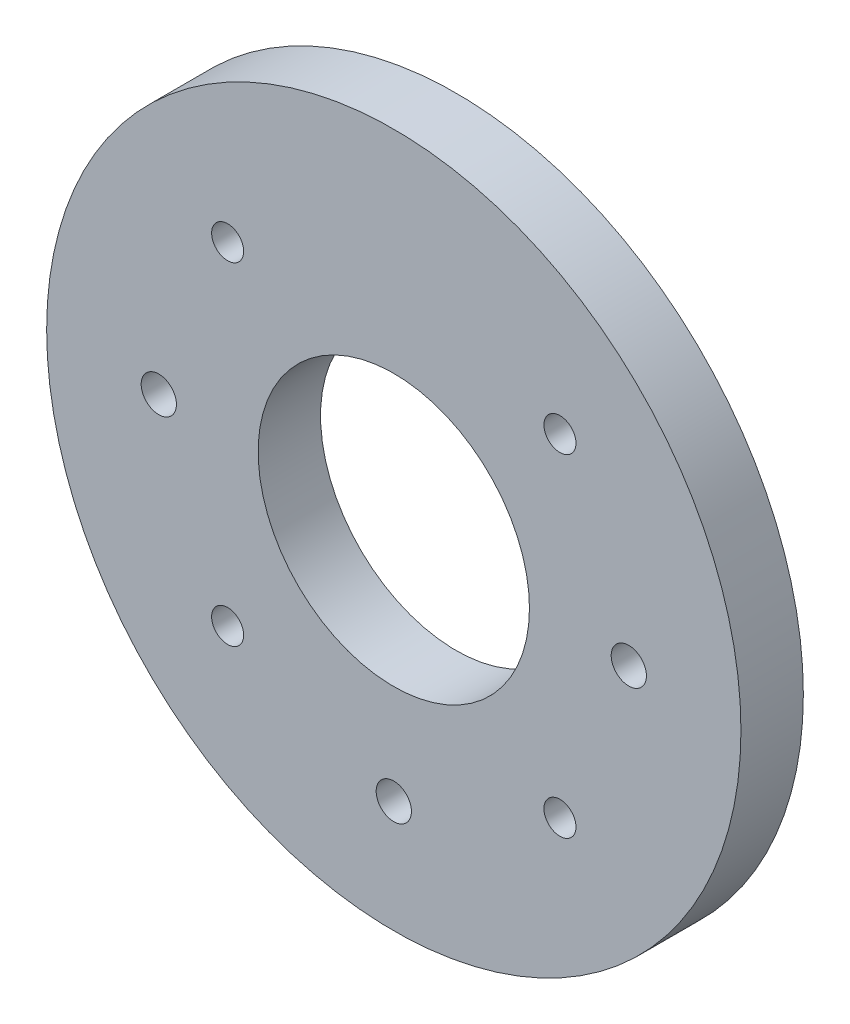
SolidWorks part; units mm, degrees
material "Acrylic (Medium-high impact)"
ref_plane "Front Plane" through (0, 0, 0) normal (0, 0, 1) x (1, 0, 0)
ref_plane "Top Plane" through (0, 0, 0) normal (0, 1, 0) x (1, 0, 0)
ref_plane "Right Plane" through (0, 0, 0) normal (1, 0, 0) x (0, 0, -1)
sketch "Sketch1" plane through (0, 0, 0) normal (0, 0, 1) x (1, 0, 0)
  line L0 (0, 32.5) -> (0, -32.5) construction
  line L1 (-32.5, 0) -> (32.5, 0) construction
  line L2 (12.7, 0) -> (22, 0) construction
  circle A0 centre (0, 0) radius 32.5
  circle A1 centre (0, 0) radius 12.7
  circle A2 centre (22, 0) radius 1.65
  circle A3 centre (0, -22) radius 1.65
  circle A4 centre (-22, 0) radius 1.65
  circle A5 centre (0, 22) radius 1.65 [skipped]
  point P20 (0, 0)
  point P29 (0, 0)
  dimension "D1" = 65
  dimension "D2" = 25.4
  dimension "D4" = 3.3
  dimension "D3" = 22
  dimension "D5" = 4
extrude "Boss-Extrude1" add sketch "Sketch1" along normal blind 5.842
sketch "Sketch2" plane through (0, 0, 5.842) normal (0, 0, 1) x (1, 0, 0)
  line L0 (0, 0) -> (-15.5563, -15.5563) construction
  line L1 (0, -22) -> (0, 0) construction
  circle A0 centre (-15.5563, -15.5563) radius 1.5
  circle A1 centre (-15.5563, 15.5563) radius 1.5
  circle A2 centre (15.5563, 15.5563) radius 1.5
  circle A3 centre (15.5563, -15.5563) radius 1.5
  point P15 (0, 0)
  dimension "D1" = 3
  dimension "D2" = 45
  dimension "D3" = 4
extrude "Cut-Extrude2" cut sketch "Sketch2" against normal through all
